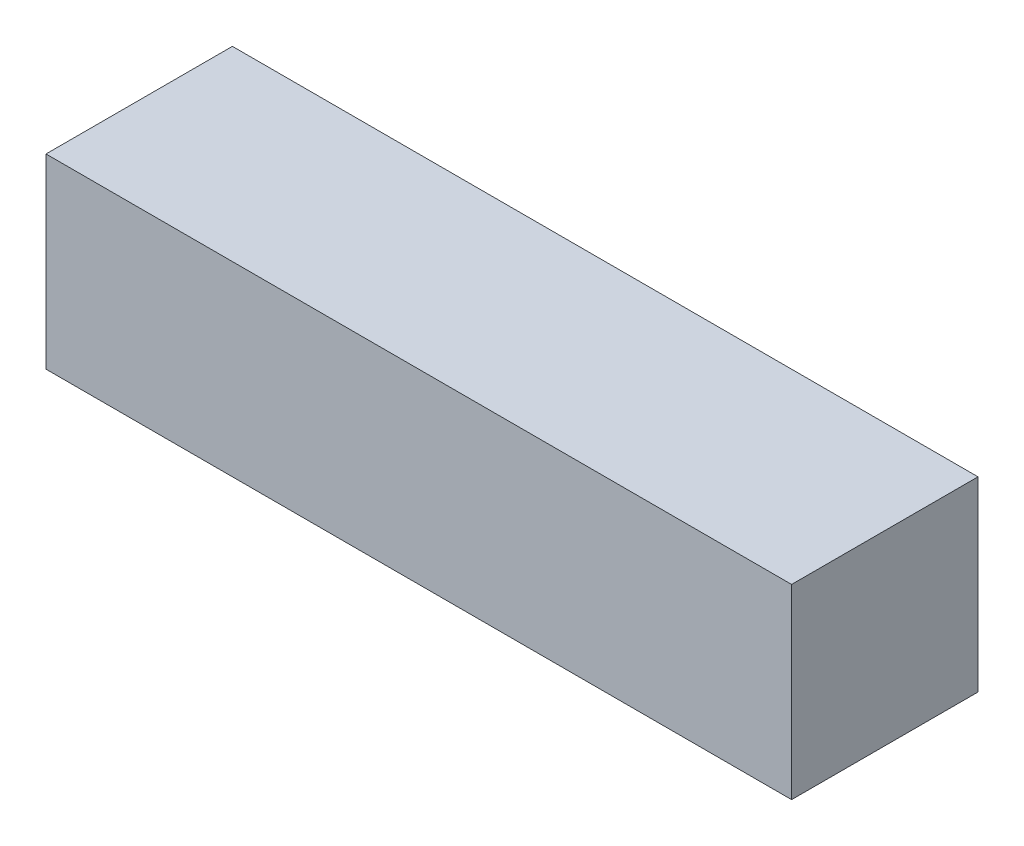
SolidWorks part; units mm, degrees
ref_plane "Front Plane" through (0, 0, 0) normal (0, 0, 1) x (1, 0, 0)
ref_plane "Top Plane" through (0, 0, 0) normal (0, 1, 0) x (1, 0, 0)
ref_plane "Right Plane" through (0, 0, 0) normal (1, 0, 0) x (0, 0, -1)
sketch "Sketch1" plane through (0, 0, 0) normal (0, 1, 0) x (1, 0, 0)
  line L1 (0, 0) -> (76.2, 0)
  line L2 (0, 0) -> (0, 19.05)
  line L3 (0, 19.05) -> (76.2, 19.05)
  line L4 (76.2, 0) -> (76.2, 19.05)
  line L5 (0, 0) -> (76.2, 19.05) construction
  line L6 (0, 19.05) -> (76.2, 0) construction
  point P4 (38.1, 9.525)
  dimension "D1" = 19.05
  dimension "D2" = 76.2
extrude "Boss-Extrude1" add sketch "Sketch1" along normal blind 19.05
